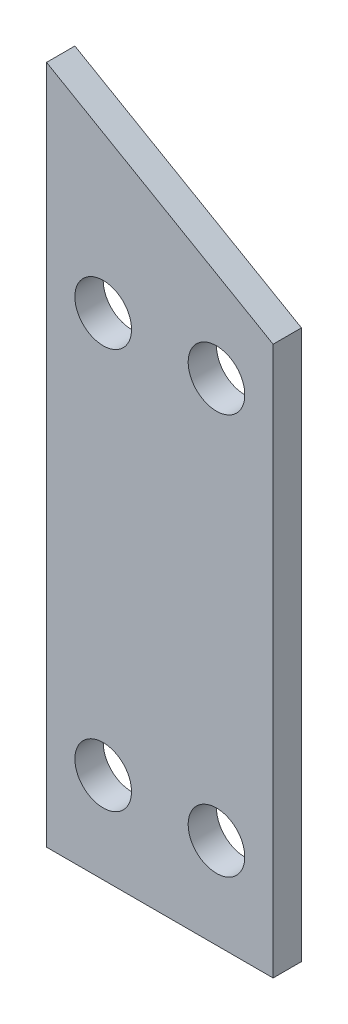
SolidWorks part; units mm, degrees
ref_plane "Front Plane" through (0, 0, 0) normal (0, 0, 1) x (1, 0, 0)
ref_plane "Top Plane" through (0, 0, 0) normal (0, 1, 0) x (1, 0, 0)
ref_plane "Right Plane" through (0, 0, 0) normal (1, 0, 0) x (0, 0, -1)
sketch "Sketch1" plane through (0, 0, 0) normal (0, 0, 1) x (1, 0, 0)
  line L0 (0, 0) -> (-38.1, 0)
  line L1 (-38.1, 0) -> (-38.1, 114.3)
  line L2 (-38.1, 114.3) -> (0, 92.303)
  line L3 (0, 92.303) -> (0, 0)
  line L4 (-38.1, 9.6919) -> (0, 9.6919) construction
  line L5 (-19.05, 15.24) -> (0, 15.24) construction
  circle A0 centre (-28.575, 15.24) radius 4.7625
  circle A1 centre (-9.525, 15.24) radius 4.7625
  circle A2 centre (-28.575, 82.55) radius 4.7625
  circle A3 centre (-9.525, 82.55) radius 4.7625
  point P13 (-9.525, 15.24)
  point P16 (-28.575, 79.603)
  point P18 (-19.05, 9.6919)
  dimension "D4" = 9.525
  dimension "D7" = 9.525
  dimension "D1" = 60
  dimension "D2" = 114.3
  dimension "D3" = 38.1
  dimension "D5" = 19.05
  dimension "D6" = 15.24
  dimension "D8" = 19.05
  dimension "D9" = 82.55
extrude "Boss-Extrude1" add sketch "Sketch1" along normal blind 4.7625
